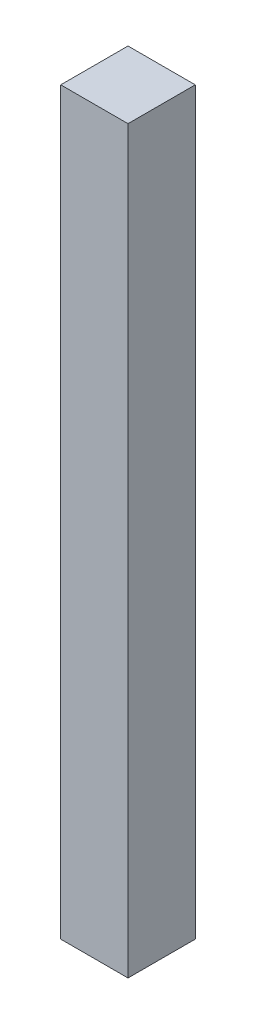
SolidWorks part; units mm, degrees
ref_plane "前基準面" through (0, 0, 0) normal (0, 0, 1) x (1, 0, 0)
ref_plane "上基準面" through (0, 0, 0) normal (0, 1, 0) x (1, 0, 0)
ref_plane "右基準面" through (0, 0, 0) normal (1, 0, 0) x (0, 0, -1)
sketch "草圖1" plane through (0, 0, 0) normal (0, 1, 0) x (1, 0, 0)
  line L1 (-10, 10) -> (10, 10)
  line L2 (-10, 10) -> (-10, -10)
  line L3 (-10, -10) -> (10, -10)
  line L4 (10, 10) -> (10, -10)
  line L5 (0, -10) -> (0, 10) construction
  line L6 (-10, 0) -> (10, 0) construction
  point P0 (0, 0)
  dimension "D1" = 20
  dimension "D2" = 20
extrude "填料-伸長1" add sketch "草圖1" along normal blind 220
